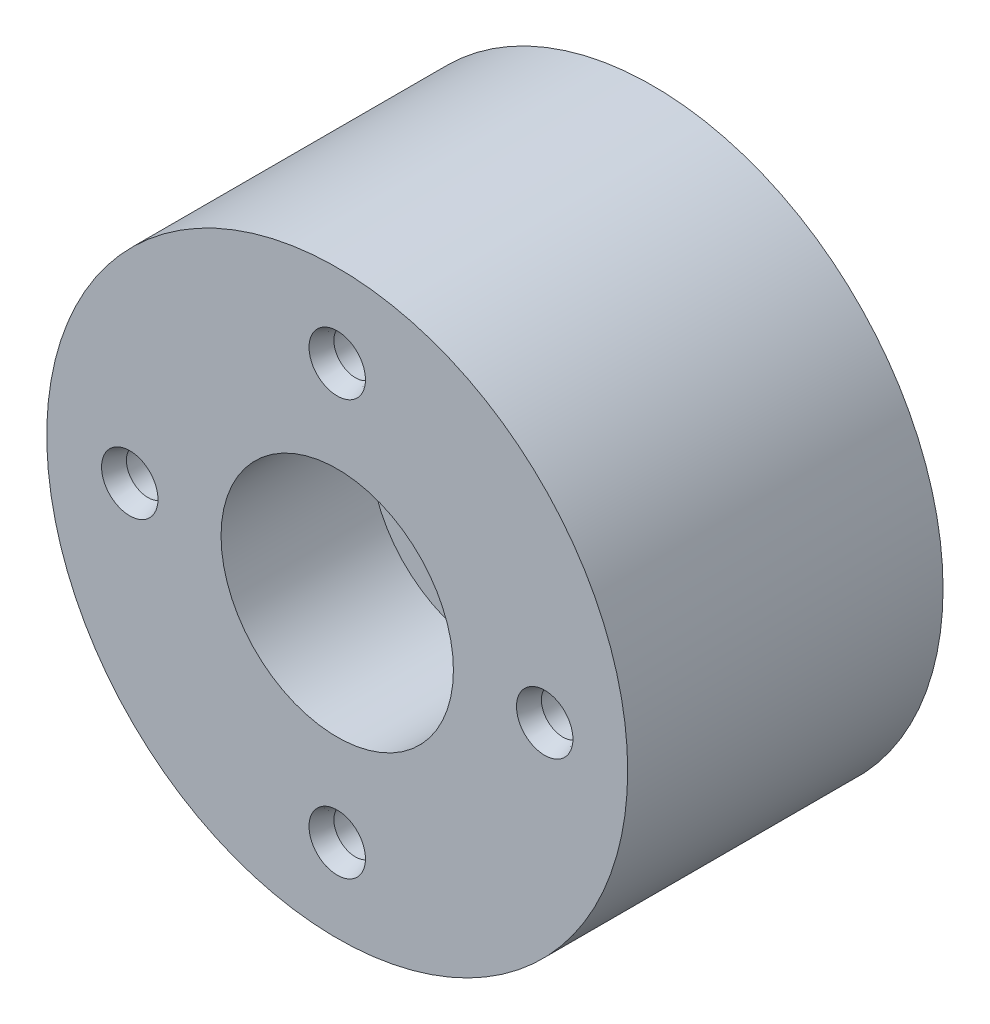
SolidWorks part; units mm, degrees
ref_plane "前视基准面" through (0, 0, 0) normal (0, 0, 1) x (1, 0, 0)
ref_plane "上视基准面" through (0, 0, 0) normal (0, 1, 0) x (1, 0, 0)
ref_plane "右视基准面" through (0, 0, 0) normal (1, 0, 0) x (0, 0, -1)
other "Configuration Table"
sketch "草图1" plane through (0, 0, 0) normal (0, 0, 1) x (1, 0, 0)
  circle A0 centre (0, 0) radius 17.5
extrude "凸台-拉伸1" add sketch "草图1" against normal blind 19
sketch "草图2" plane through (0, 0, 0) normal (0, 0, 1) x (1, 0, 0)
  circle A0 centre (12.5, 0) radius 1.3
  circle A1 centre (0, -12.5) radius 1.3
  circle A2 centre (-12.5, 0) radius 1.3
  circle A3 centre (0, 12.5) radius 1.3
  point P11 (0, 0)
  dimension "D1" = 4
extrude "切除-拉伸1" cut sketch "草图2" against normal blind 8
sketch "草图4" plane through (0, 0, 0) normal (0, 0, 1) x (1, 0, 0)
  circle A0 centre (0, 0) radius 7
extrude "切除-拉伸3" cut sketch "草图4" against normal offset from surface (9 mm away) 10 up to face at (17.5, 0, -19)
sketch "草图5" plane through (0, 0, -9) normal (0, 0, 1) x (1, 0, 0)
  circle A0 centre (0, 0) radius 5.55
extrude "切除-拉伸4" cut sketch "草图5" against normal up to surface (10 mm away) up to face at (17.5, 0, -19)
sketch "草图6" plane through (0, 0, -19) normal (0, 0, -1) x (-1, 0, 0)
  line L0 (0, 0) -> (8.0544, 4.0158) construction
  line L5 (7.0951, 5.9399) -> (14.5834, 9.6734)
  line L6 (9.0137, 2.0917) -> (16.502, 5.8252)
  line L8 (0, 0) -> (30.1626, 0) construction
  arc A0 (7.0951, 5.9399) -> (9.0137, 2.0917) centre (8.0544, 4.0158) ccw
  arc A7 (16.502, 5.8252) -> (14.5834, 9.6734) centre (0, 0) ccw
extrude "切除-拉伸6" cut sketch "草图6" against normal blind 8
fillet "圆角2" radius 0.8 3 edges at (-12.7579, 3.9584, -11) (-6.1303, 3.0565, -11) (-10.8392, 7.8067, -11)
chamfer "倒角1" distance 0.9 angle 60 1 edges at (5.55, 0, -19)
chamfer "倒角2" distance 0.4 angle 70 4 edges at (-11.2, 0, 0) (1.3, -12.5, 0) (13.8, 0, 0) (1.3, 12.5, 0)
fillet "圆角3" radius 0.8 5 edges at (-16.502, 5.8252, -15.4) (-16.3995, 6.108, -11.1764) (-15.6614, 7.8085, -11) (-14.6791, 9.5275, -11.3028) (-14.5834, 9.6734, -15.4)
